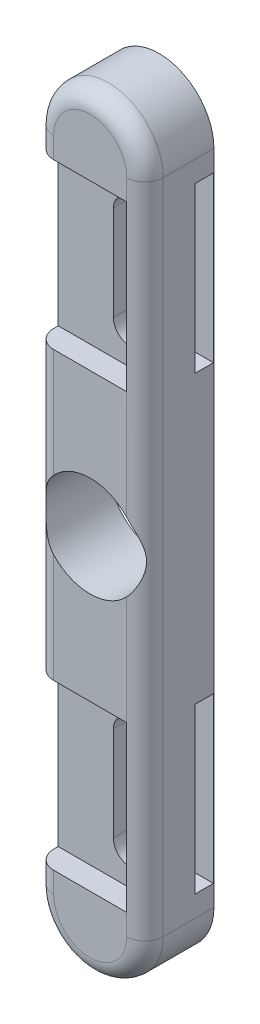
SolidWorks part; units mm, degrees
ref_plane "Alzado" through (0, 0, 0) normal (0, 0, 1) x (1, 0, 0)
ref_plane "Planta" through (0, 0, 0) normal (0, 1, 0) x (1, 0, 0)
ref_plane "Vista lateral" through (0, 0, 0) normal (1, 0, 0) x (0, 0, -1)
sketch "Croquis1" plane through (0, 0, 0) normal (0, 0, 1) x (1, 0, 0)
  line L0 (58.9, -7.25) -> (58.9, 64.75) construction
  line L1 (52.9, -7.25) -> (52.9, 64.75)
  line L2 (64.9, -7.25) -> (64.9, 64.75)
  line L3 (-23.1, 70.75) -> (58.9, 70.75) construction
  arc A0 (52.9, -7.25) -> (64.9, -7.25) centre (58.9, -7.25) ccw
  arc A1 (64.9, 64.75) -> (52.9, 64.75) centre (58.9, 64.75) ccw
  arc A3 (58.9, -13.25) -> (64.9, -7.25) centre (58.9, -7.25) ccw construction
  point P4 (58.9, 28.75)
  dimension "D1" = 6
extrude "Saliente-Extruir1" add sketch "Croquis1" along normal up to surface (7.55 mm away) contours A0 L2 A1 L1
fillet "Redondeo1" radius 2 4 edges at (58.9, 70.75, 7.55) (64.9, 28.75, 7.55) (58.9, -13.25, 7.55) (52.9, 28.75, 7.55)
sketch "Croquis2" plane through (0, 0, 7.55) normal (0, 0, 1) x (1, 0, 0)
  line L0 (46.8348, -4.9448) -> (62.9, -4.9448)
  line L1 (46.8348, -4.9448) -> (46.8348, 13.0552)
  line L2 (62.9, -4.9448) -> (62.9, 13.0552)
  line L3 (46.8348, 13.0552) -> (62.9, 13.0552)
  line L5 (62.9, -7.25) -> (62.9, 64.75) construction
  line L6 (62.9, 28.75) -> (50062.9, 28.75) construction
  line L7 (62.9, 62.4448) -> (62.9, 44.4448)
  line L8 (46.8348, 44.4448) -> (62.9, 44.4448)
  line L9 (46.8348, 62.4448) -> (46.8348, 44.4448)
  line L10 (46.8348, 62.4448) -> (62.9, 62.4448)
  point P8 (62.9, 28.75)
  dimension "D1" = 18
extrude "Cortar-Extruir1" cut sketch "Croquis2" against normal blind 2.5
sketch "Croquis3" plane through (0, 0, 7.55) normal (0, 0, 1) x (1, 0, 0)
  line L0 (58.9, 64.75) -> (58.9, -7.25) construction
  circle A0 centre (58.9, 28.75) radius 5.5
  dimension "D1" = 11
extrude "Cortar-Extruir2" cut sketch "Croquis3" against normal through all contours A0
sketch "Croquis4" plane through (64.9, 0, 0) normal (1, 0, 0) x (0, 0, -1)
  line L0 (-7.55, 62.4448) -> (0, 62.4448) construction
  line L1 (0, 64.75) -> (0, -7.25) construction
  line L2 (-7.55, 44.4448) -> (0, 44.4448) construction
  line L3 (-7.55, 13.0552) -> (0, 13.0552) construction
  line L4 (-7.55, -4.9448) -> (0, -4.9448) construction
  line L5 (-5.55, 28.75) -> (0, 28.75) construction
  line L6 (-5.55, 64.75) -> (-5.55, -7.25) construction
  line L7 (-5.05, -4.9448) -> (-5.05, 13.0552) construction
  line L8 (-2.05, 13.0552) -> (-0.05, 13.0552)
  line L9 (-2.05, 13.0552) -> (-2.05, -4.9448)
  line L10 (-2.05, -4.9448) -> (-0.05, -4.9448)
  line L11 (-0.05, 13.0552) -> (-0.05, -4.9448)
  line L12 (-2.05, 62.4448) -> (-0.05, 62.4448)
  line L13 (-2.05, 44.4448) -> (-0.05, 44.4448)
  line L14 (-0.05, 44.4448) -> (-0.05, 62.4448)
  line L15 (-2.05, 44.4448) -> (-2.05, 62.4448)
  dimension "D1" = 3
  dimension "D2" = 2
extrude "Cortar-Extruir3" cut sketch "Croquis4" against normal blind 6.5
sketch "Croquis5" plane through (0, 0, 5.05) normal (0, 0, 1) x (1, 0, 0)
  line L0 (60.741, 9.2452) -> (60.741, 50009.2452) construction
  line L1 (52.9, 28.75) -> (64.9, 28.75) construction
  line L2 (52.9, 13.0552) -> (52.9, 44.4448) construction
  line L3 (64.9, 64.75) -> (64.9, -7.25) construction
  line L4 (60.741, 9.2452) -> (60.741, -1.1348) construction
  line L5 (62.541, 9.2452) -> (62.541, -1.1348)
  line L6 (58.941, 9.2452) -> (58.941, -1.1348)
  line L7 (62.9, 13.0552) -> (54.9, 13.0552) construction
  line L8 (60.741, 48.2548) -> (60.741, 58.6348) construction
  line L9 (62.541, 48.2548) -> (62.541, 58.6348)
  line L10 (58.941, 48.2548) -> (58.941, 58.6348)
  arc A0 (62.541, 9.2452) -> (58.941, 9.2452) centre (60.741, 9.2452) ccw
  arc A1 (58.941, -1.1348) -> (62.541, -1.1348) centre (60.741, -1.1348) ccw
  arc A2 (62.541, 48.2548) -> (58.941, 48.2548) centre (60.741, 48.2548) cw
  arc A3 (58.941, 58.6348) -> (62.541, 58.6348) centre (60.741, 58.6348) cw
  point P11 (60.741, 4.0552)
  point P25 (60.741, 53.4448)
  dimension "D1" = 1.8
  dimension "D2" = 10.38
  dimension "D3" = 3.81
extrude "Cortar-Extruir4" cut sketch "Croquis5" against normal through all
